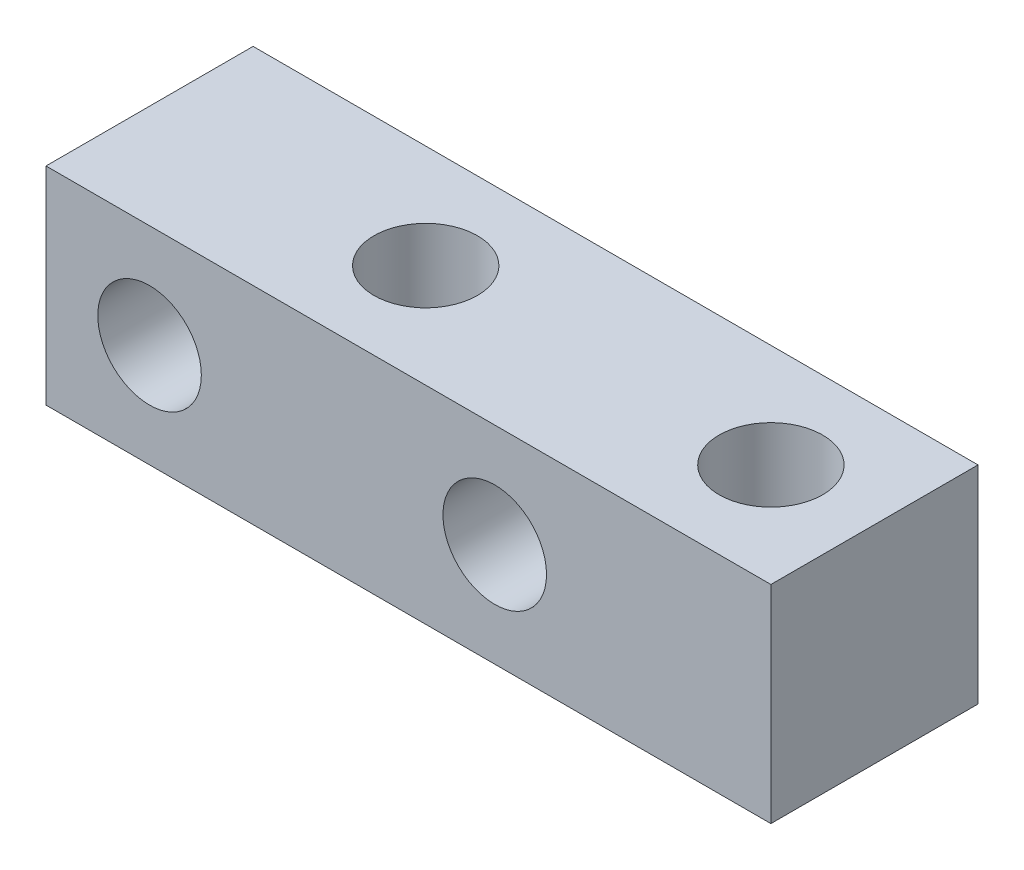
SolidWorks part; units mm, degrees
material "6061 合金"
ref_plane "前视基准面" through (0, 0, 0) normal (0, 0, 1) x (1, 0, 0)
ref_plane "上视基准面" through (0, 0, 0) normal (0, 1, 0) x (1, 0, 0)
ref_plane "右视基准面" through (0, 0, 0) normal (1, 0, 0) x (0, 0, -1)
other "Configuration Table"
sketch "草图1" plane through (0, 0, 0) normal (0, 0, 1) x (1, 0, 0)
  line L0 (-12.4936, 7.9916) -> (8.5064, 7.9916)
  line L1 (8.5064, 7.9916) -> (8.5064, 1.9916)
  line L2 (8.5064, 1.9916) -> (-12.4936, 1.9916)
  line L3 (-12.4936, 1.9916) -> (-12.4936, 7.9916)
  circle A0 centre (-9.4936, 4.9916) radius 1.5
  circle A1 centre (0.5064, 4.9916) radius 1.5
  dimension "D3" = 3
  dimension "D4" = 3
  dimension "D5" = 3
  dimension "D6" = 10
  dimension "D1" = 21
  dimension "D2" = 6
extrude "凸台-拉伸1" add sketch "草图1" along normal blind 6
sketch "草图2" plane through (0, 1.9916, 0) normal (0, -1, 0) x (1, 0, 0)
  line L0 (8.5064, 6) -> (8.5064, 0) construction
  circle A0 centre (5.5064, 3) radius 1.5
  circle A1 centre (-4.4936, 3) radius 1.5
  dimension "D1" = 3
  dimension "D2" = 3
  dimension "D3" = 10
extrude "切除-拉伸1" cut sketch "草图2" against normal blind 6
